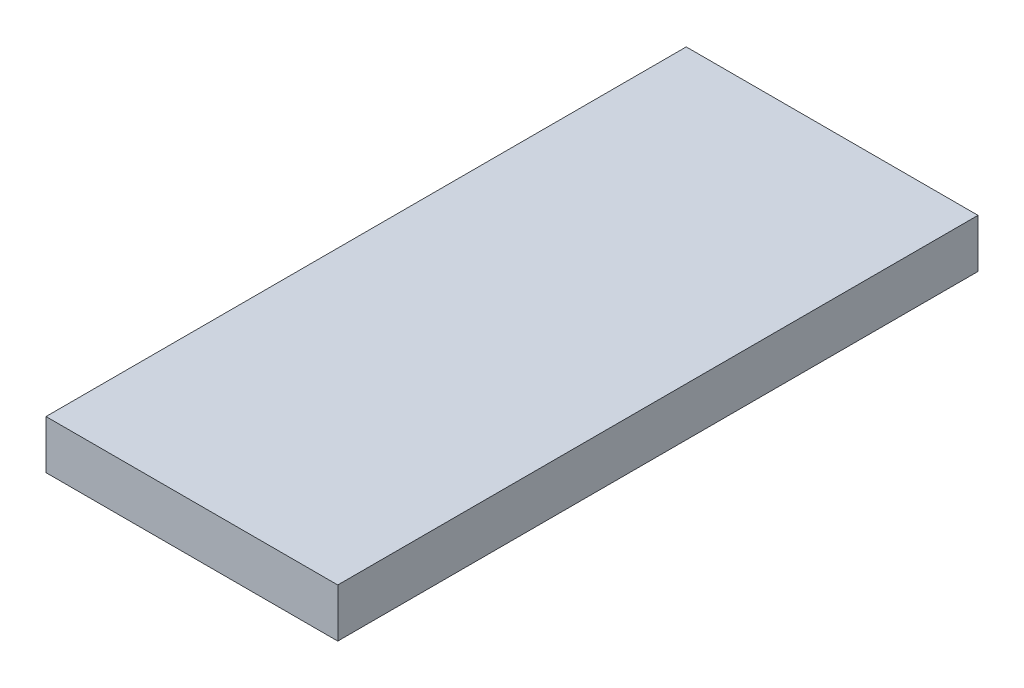
SolidWorks part; units mm, degrees
material "Silicon Rubber"
ref_plane "Front Plane" through (0, 0, 0) normal (0, 0, 1) x (1, 0, 0)
ref_plane "Top Plane" through (0, 0, 0) normal (0, 1, 0) x (1, 0, 0)
ref_plane "Right Plane" through (0, 0, 0) normal (1, 0, 0) x (0, 0, -1)
sketch "Sketch1" plane through (0, 0, 0) normal (0, 1, 0) x (1, 0, 0)
  line L0 (0, 0) -> (0, 39.5)
  line L1 (0, 39.5) -> (18, 39.5)
  line L2 (18, 39.5) -> (18, 0)
  line L3 (18, 0) -> (0, 0)
extrude "Boss-Extrude1" add sketch "Sketch1" along normal blind 3
